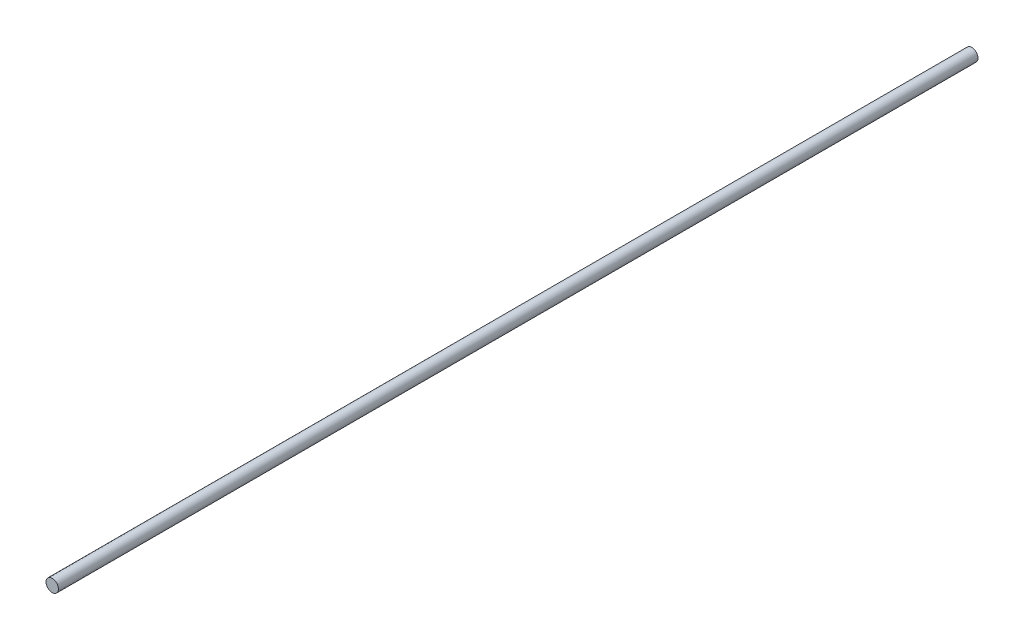
SolidWorks part; units mm, degrees
ref_plane "Alzado" through (0, 0, 0) normal (0, 0, 1) x (1, 0, 0)
ref_plane "Planta" through (0, 0, 0) normal (0, 1, 0) x (1, 0, 0)
ref_plane "Vista lateral" through (0, 0, 0) normal (1, 0, 0) x (0, 0, -1)
sketch "Croquis1" plane through (0, 0, 0) normal (0, 0, 1) x (1, 0, 0)
  circle A0 centre (0, 0) radius 4.05
  dimension "D1" = 8.1
extrude "Saliente-Extruir1" add sketch "Croquis1" along normal blind 600
